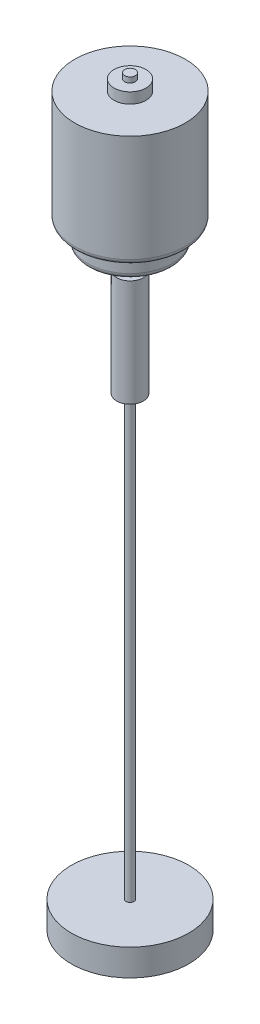
SolidWorks part; units mm, degrees
ref_plane "Alzado" through (0, 0, 0) normal (0, 0, 1) x (1, 0, 0)
ref_plane "Planta" through (0, 0, 0) normal (0, 1, 0) x (1, 0, 0)
ref_plane "Vista lateral" through (0, 0, 0) normal (1, 0, 0) x (0, 0, -1)
sketch "Croquis1" plane through (0, 0, 0) normal (0, 0, 1) x (1, 0, 0)
  line L0 (0, 0) -> (0, 26.5)
  line L1 (0, 26.5) -> (10.35, 26.5)
  line L2 (10.35, 26.5) -> (10.35, 5.5)
  line L3 (10.35, 5.5) -> (7.9, 5.5)
  line L4 (7.9, 5.5) -> (7.9, 1.5)
  line L5 (7.9, 1.5) -> (3, 1.5)
  line L6 (3, 1.5) -> (3, 0)
  line L7 (3, 0) -> (0, 0)
  line L8 (0, 14.9515) -> (0, 22281.2421) construction
  dimension "D1" = 20.7
  dimension "D2" = 15.8
  dimension "D3" = 6
  dimension "D4" = 26.5
  dimension "D5" = 21
  dimension "D6" = 4
revolve "Revolución1" add sketch "Croquis1" angle 360 about L8
sketch "Croquis2" plane through (0, 26.5, 0) normal (0, 1, 0) x (1, 0, 0)
  circle A0 centre (0, 0) radius 3
  dimension "D1" = 6
extrude "Saliente-Extruir1" add sketch "Croquis2" along normal blind 2
sketch "Croquis3" plane through (0, 28.5, 0) normal (0, 1, 0) x (1, 0, 0)
  circle A0 centre (0, 0) radius 1
  dimension "D1" = 2
extrude "Saliente-Extruir2" add sketch "Croquis3" along normal blind 1
sketch "Croquis4" plane through (0, 0, 0) normal (0, -1, 0) x (1, 0, 0)
  circle A0 centre (0, 0) radius 1
  dimension "D1" = 2
extrude "Saliente-Extruir3" add sketch "Croquis4" along normal blind 2.5
sketch "Croquis5" plane through (0, -2.5, 0) normal (0, -1, 0) x (1, 0, 0)
  circle A0 centre (0, 0) radius 2.5
  dimension "D1" = 5
extrude "Saliente-Extruir4" add sketch "Croquis5" along normal blind 20
sketch "Croquis6" plane through (0, -22.5, 0) normal (0, -1, 0) x (1, 0, 0)
  circle A0 centre (0, 0) radius 0.75
  dimension "D1" = 1.5
extrude "Saliente-Extruir5" add sketch "Croquis6" along normal blind 82
sketch "Croquis7" plane through (0, -104.5, 0) normal (0, -1, 0) x (1, 0, 0)
  circle A0 centre (0, 0) radius 11
  dimension "D1" = 22
extrude "Saliente-Extruir6" add sketch "Croquis7" along normal blind 5
fillet "Redondeo1" radius 1 3 edges at (0, 1.5, -7.9) (0, 5.5, -7.9) (0, 5.5, -10.35)
